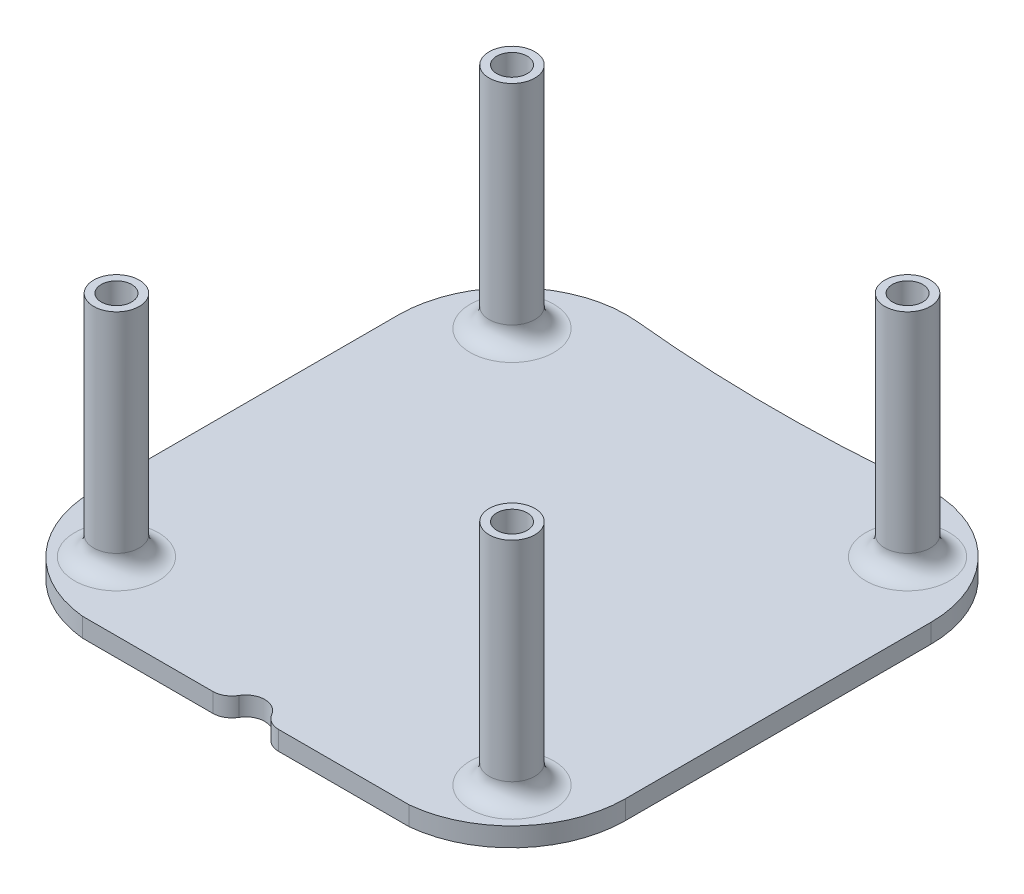
SolidWorks part; units mm, degrees
ref_plane "Front Plane" through (0, 0, 0) normal (0, 0, 1) x (1, 0, 0)
ref_plane "Top Plane" through (0, 0, 0) normal (0, 1, 0) x (1, 0, 0)
ref_plane "Right Plane" through (0, 0, 0) normal (1, 0, 0) x (0, 0, -1)
sketch "Sketch2" plane through (0, 0, 0) normal (0, 1, 0) x (1, 0, 0)
  line L0 (-10.5361, -2.0967) -> (-10.5361, 65.9963) construction
  line L1 (-53.5088, -72.0967) -> (32.4366, -72.0967)
  line L2 (-80.5361, -42.2444) -> (-80.5361, 38.0509)
  line L3 (59.4639, -42.2444) -> (59.4639, 38.0509)
  line L4 (-10.5361, -2.0967) -> (79.7046, -2.0967) construction
  line L5 (-71.7102, 59.3032) -> (50.638, -63.4966) construction
  arc A0 (-47.5634, 67.9033) -> (-80.5361, 38.0509) centre (-50.5361, 38.0509) ccw
  arc A1 (59.4639, 38.0509) -> (29.516, 68.0509) centre (29.4639, 38.0509) ccw
  arc A2 (29.516, 68.0509) -> (-47.5634, 67.9033) centre (-9.7397, 441.8979) cw
  arc A3 (-53.5088, -72.0967) -> (-80.5361, -42.2444) centre (-50.5361, -42.2444) cw
  arc A4 (59.4639, -42.2444) -> (32.4366, -72.0967) centre (29.4639, -42.2444) cw
  point P0 (-10.5361, -2.0967)
  dimension "D4" = 30
  dimension "D5" = 30
  dimension "D1" = 72.0967
  dimension "D2" = 59.4639
  dimension "D3" = 140
  dimension "D6" = 80
  dimension "D7" = 40
  dimension "D8" = 140
extrude "Boss-Extrude1" add sketch "Sketch2" along normal blind 5
sketch "Sketch3" plane through (0, 5, 0) normal (0, 1, 0) x (1, 0, 0)
  line L1 (59.4639, -2.0967) -> (-80.5361, -2.0967) construction
  line L2 (59.4639, -42.2444) -> (59.4639, 38.0509) construction
  line L3 (-80.5361, 38.0509) -> (-80.5361, -42.2444) construction
  line L4 (-10.5361, -72.0967) -> (-10.5361, 69.266) construction
  line L5 (-53.5088, -72.0967) -> (32.4366, -72.0967) construction
  circle A0 centre (41.4639, 49.9033) radius 6
  circle A1 centre (41.4639, 49.9033) radius 2
  circle A2 centre (-62.5361, 49.9033) radius 2
  circle A3 centre (-62.5361, 49.9033) radius 6
  circle A4 centre (-62.5361, -54.0967) radius 6
  circle A5 centre (-62.5361, -54.0967) radius 2
  circle A6 centre (41.4639, -54.0967) radius 2
  circle A7 centre (41.4639, -54.0967) radius 6
  dimension "D1" = 12
  dimension "D2" = 4
  dimension "D3" = 52
  dimension "D4" = 52
extrude "Boss-Extrude2" add sketch "Sketch3" along normal blind 60
sketch "Sketch4" plane through (0, 65, 0) normal (0, 1, 0) x (1, 0, 0)
  circle A0 centre (41.4639, 49.9033) radius 4
  circle A2 centre (-62.5361, 49.9033) radius 4
  circle A4 centre (-62.5361, -54.0967) radius 4
  circle A6 centre (41.4639, -54.0967) radius 4
  dimension "D1" = 8
  dimension "D3" = 8
  dimension "D5" = 8
  dimension "D7" = 8
extrude "Cut-Extrude2" cut sketch "Sketch4" against normal blind 20
fillet "Fillet1" radius 5 4 edges at (41.4639, 5, 48.0967) (-62.5361, 5, 48.0967) (-62.5361, 5, -55.9033) (41.4639, 5, -55.9033)
sketch "Sketch5" plane through (0, 5, 0) normal (0, 1, 0) x (1, 0, 0)
  line L0 (-53.5088, -72.0967) -> (32.4366, -72.0967) construction
  circle A0 centre (-10.5361, -72.0967) radius 5
  dimension "D1" = 10
extrude "Cut-Extrude3" cut sketch "Sketch5" against normal blind 10
fillet "Fillet2" radius 5 2 edges at (-5.5361, 2.5, 72.0967) (-15.5361, 2.5, 72.0967)
